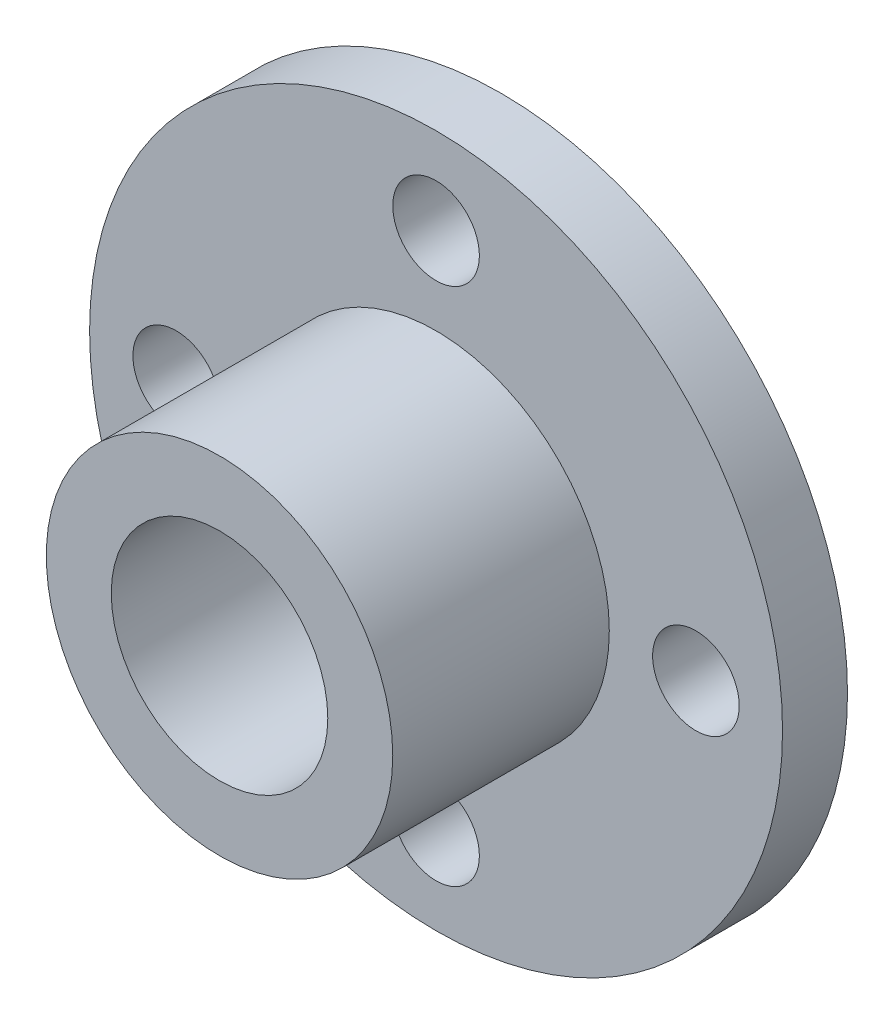
SolidWorks part; units mm, degrees
ref_plane "前视基准面" through (0, 0, 0) normal (0, 0, 1) x (1, 0, 0)
ref_plane "上视基准面" through (0, 0, 0) normal (0, 1, 0) x (1, 0, 0)
ref_plane "右视基准面" through (0, 0, 0) normal (1, 0, 0) x (0, 0, -1)
other "Configuration Table"
sketch "草图1" plane through (0, 0, 0) normal (0, 0, 1) x (1, 0, 0)
  circle A0 centre (0, 0) radius 16
  dimension "D1" = 32
extrude "凸台-拉伸1" add sketch "草图1" along normal blind 3
sketch "草图2" plane through (0, 0, 3) normal (0, 0, 1) x (1, 0, 0)
  circle A0 centre (0, 0) radius 8
  dimension "D1" = 16
extrude "凸台-拉伸2" add sketch "草图2" along normal blind 10
sketch "草图3" plane through (0, 0, 13) normal (0, 0, 1) x (1, 0, 0)
  circle A0 centre (0, 0) radius 5
  circle A2 centre (0, 12) radius 2
  circle A3 centre (12, 0) radius 2
  circle A4 centre (0, -12) radius 2
  circle A5 centre (-12, 0) radius 2
  point P15 (0, 0)
  dimension "D1" = 10
  dimension "D3" = 4
  dimension "D4" = 4
extrude "切除-拉伸1" cut sketch "草图3" against normal up to next
